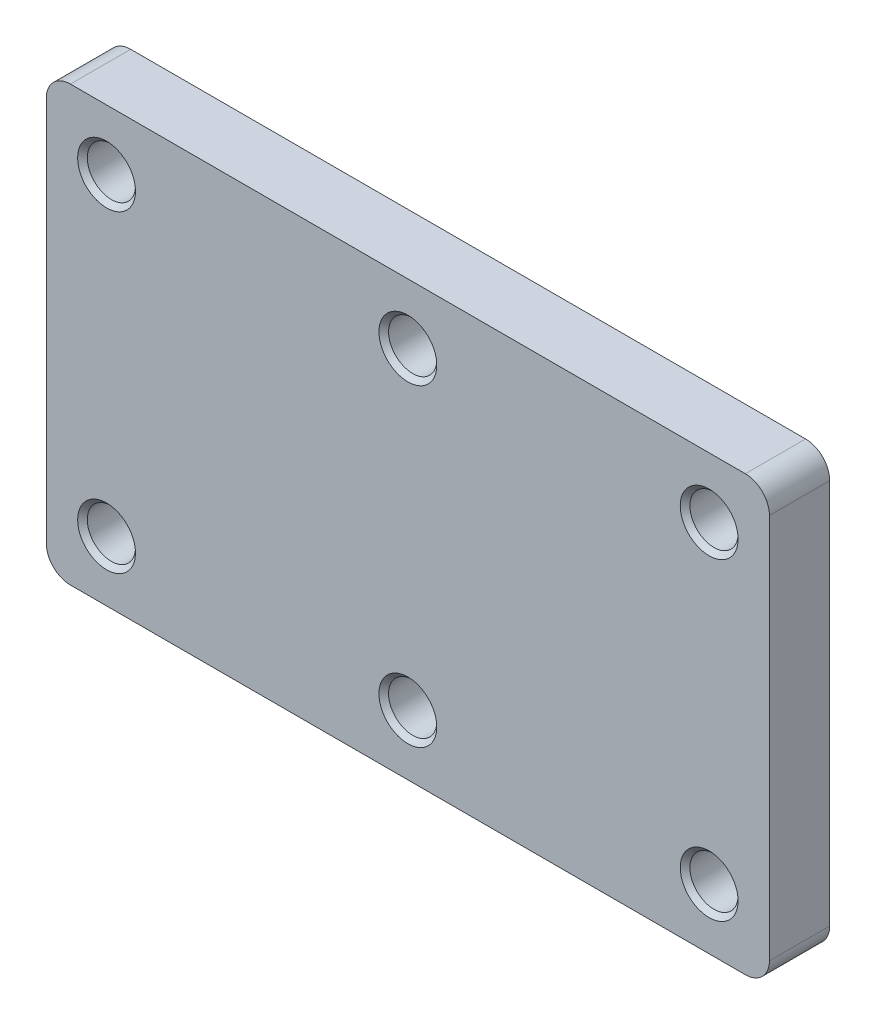
SolidWorks part; units mm, degrees
ref_plane "前基準面" through (0, 0, 0) normal (0, 0, 1) x (1, 0, 0)
ref_plane "上基準面" through (0, 0, 0) normal (0, 1, 0) x (1, 0, 0)
ref_plane "右基準面" through (0, 0, 0) normal (1, 0, 0) x (0, 0, -1)
sketch "草圖1" plane through (0, 0, 0) normal (0, 0, 1) x (1, 0, 0)
  line L1 (0, 0) -> (300, 0)
  line L2 (0, 0) -> (0, 180)
  line L3 (0, 180) -> (300, 180)
  line L4 (300, 0) -> (300, 180)
  dimension "D1" = 180
  dimension "D2" = 300
extrude "填料-伸長1" add sketch "草圖1" along normal blind 25
fillet "圓角1" radius 10 4 edges at (300, 0, 12.5) (300, 180, 12.5) (0, 0, 12.5) (0, 180, 12.5)
sketch "草圖2" plane through (0, 0, 25) normal (0, 0, 1) x (1, 0, 0)
  line L0 (150, 25) -> (150, 155)
  line L1 (25, 25) -> (275, 25)
  line L2 (25, 25) -> (25, 155)
  line L3 (25, 155) -> (275, 155)
  line L4 (275, 25) -> (275, 155)
  line L5 (0, 170) -> (0, 10) construction
  line L6 (10, 0) -> (290, 0) construction
  dimension "D1" = 250
  dimension "D2" = 25
  dimension "D3" = 130
  dimension "D4" = 25
hole_wizard "Ø20.0mm 定位孔1" positions "3D草圖1" profile "草圖4" hole size "Ø20.0" standard "ISO"
sketch3d "3D草圖1"
  line L0 (25, 25, 25) -> (275, 25, 25) construction
  point P0 (25, 25, 25)
  point P3 (25, 155, 25)
  point P6 (150, 155, 25)
  point P9 (150, 25, 25)
  point P13 (275, 25, 25)
  point P16 (275, 155, 25)
  point P20 (150, 25, 25)
sketch "草圖4" plane through (25, 25, 25) normal (1, 0, 0) x (0, -1, 0)
  line L0 (0, 0) -> (0, 65.0086)
  line L1 (0, 65.0086) -> (10, 59)
  line L2 (10, 59) -> (10, 0)
  line L5 (10, 0) -> (0, 0)
  line L10 (0, 65.0086) -> (-10, 59) construction
  line L11 (0, -6.35) -> (0, 107.95) construction
  dimension "苝ふ 畖" = 20
  dimension "苝ふ瞏 " = 59
  dimension "旧繷à " = 118
hole_wizard "Ø20.0mm 定位孔2" positions "3D草圖2" profile "草圖5" hole size "Ø20.0" standard "ISO"
sketch3d "3D草圖2"
  point P0 (150, 25, 25)
sketch "草圖5" plane through (150, 25, 25) normal (1, 0, 0) x (0, -1, 0)
  line L0 (0, 0) -> (0, 65.0086)
  line L1 (0, 65.0086) -> (10, 59)
  line L2 (10, 59) -> (10, 0)
  line L5 (10, 0) -> (0, 0)
  line L10 (0, 65.0086) -> (-10, 59) construction
  line L11 (0, -6.35) -> (0, 107.95) construction
  dimension "苝ふ 畖" = 20
  dimension "苝ふ瞏 " = 59
  dimension "旧繷à " = 118
chamfer "導角1" distance 2 angle 45 12 edges at (285, 25, 25) (265, 25, 0) (285, 155, 25) (265, 155, 0) (160, 155, 25) (140, 155, 0) (35, 155, 25) (15, 155, 0) (160, 25, 25) (140, 25, 0) (35, 25, 25) (15, 25, 0)
